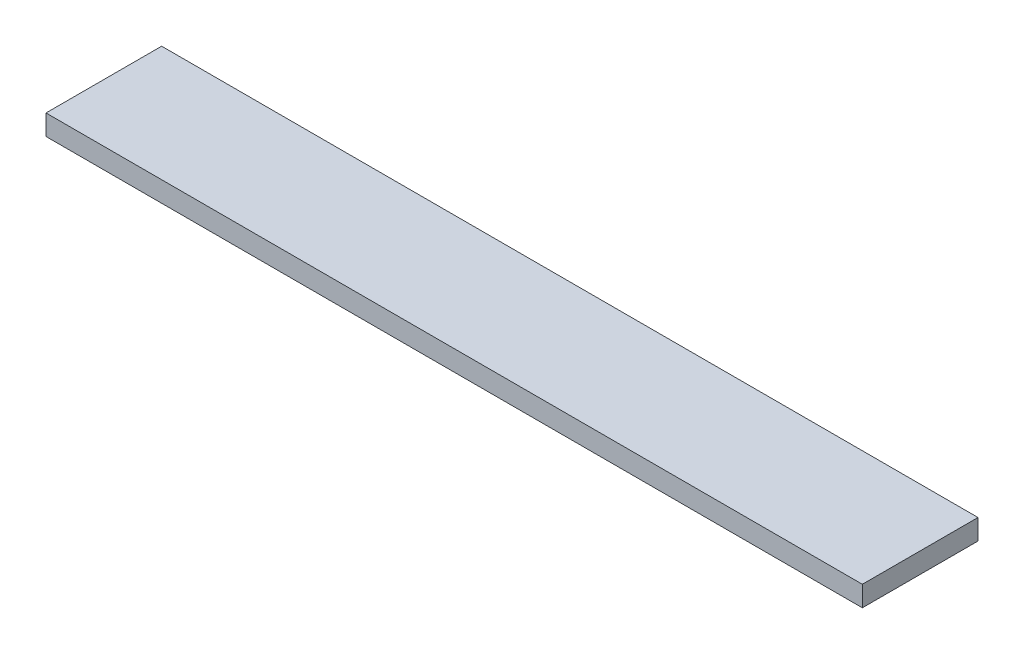
SolidWorks part; units mm, degrees
ref_plane "Alzado" through (0, 0, 0) normal (0, 0, 1) x (1, 0, 0)
ref_plane "Planta" through (0, 0, 0) normal (0, 1, 0) x (1, 0, 0)
ref_plane "Vista lateral" through (0, 0, 0) normal (1, 0, 0) x (0, 0, -1)
sketch "Croquis1" plane through (0, 0, 0) normal (0, 1, 0) x (1, 0, 0)
  line L1 (60, -8.5) -> (-60, -8.5)
  line L2 (60, -8.5) -> (60, 8.5)
  line L3 (60, 8.5) -> (-60, 8.5)
  line L4 (-60, -8.5) -> (-60, 8.5)
  line L5 (60, -8.5) -> (-60, 8.5) construction
  line L6 (60, 8.5) -> (-60, -8.5) construction
  point P0 (0, 0)
extrude "Saliente-Extruir1" add sketch "Croquis1" along normal blind 3
